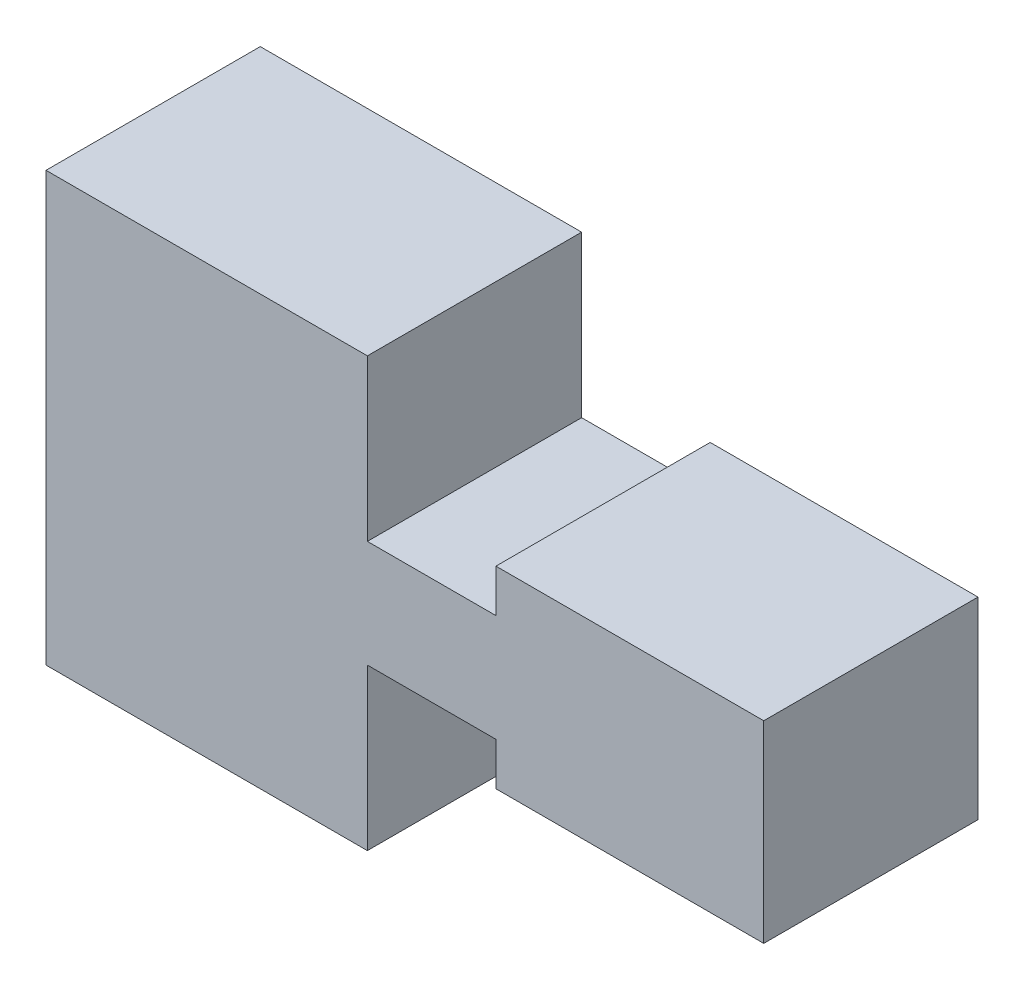
SolidWorks part; units mm, degrees
ref_plane "Front Plane" through (0, 0, 0) normal (0, 0, 1) x (1, 0, 0)
ref_plane "Top Plane" through (0, 0, 0) normal (0, 1, 0) x (1, 0, 0)
ref_plane "Right Plane" through (0, 0, 0) normal (1, 0, 0) x (0, 0, -1)
sketch "Sketch1" plane through (0, 0, 0) normal (0, 0, 1) x (1, 0, 0)
  line L0 (0, 0) -> (42.9561, 0) construction
  line L1 (-7.5, -10) -> (7.5, -10)
  line L2 (-7.5, -10) -> (-7.5, 10)
  line L3 (-7.5, 10) -> (7.5, 10)
  line L4 (7.5, -10) -> (7.5, 10)
  line L5 (-7.5, -10) -> (7.5, 10) construction
  line L6 (-7.5, 10) -> (7.5, -10) construction
  line L7 (7.5, 2.5) -> (13.5, 2.5)
  line L8 (7.5, 2.5) -> (7.5, -2.5)
  line L9 (7.5, -2.5) -> (13.5, -2.5)
  line L10 (13.5, 2.5) -> (13.5, -2.5)
  line L12 (13.5, -4.5) -> (26, -4.5)
  line L13 (13.5, -4.5) -> (13.5, 4.5)
  line L14 (13.5, 4.5) -> (26, 4.5)
  line L15 (26, -4.5) -> (26, 4.5)
  line L16 (13.5, -4.5) -> (26, 4.5) construction
  line L17 (13.5, 4.5) -> (26, -4.5) construction
  point P1 (0, 0)
  point P10 (19.75, 0)
  point P18 (0, 0)
  dimension "D1" = 20
  dimension "D2" = 5
  dimension "D3" = 15
  dimension "D4" = 6
  dimension "D5" = 12.5
  dimension "D6" = 2.5
  dimension "D7" = 2
extrude "Boss-Extrude1" add sketch "Sketch1" along normal blind 10 contours L1 L4 L3 L2 | L10 L7 L4 L9 | L12 L15 L14 L13 L10
sketch "Sketch5" plane through (-7.5, 0, 0) normal (-1, 0, 0) x (0, 0, 1)
  line L0 (0, -11.5) -> (10.0679, -11.5) construction
  line L1 (10, -10) -> (0, -10) construction
  line L2 (5, -10) -> (5, -12.7087) construction
  arc A0 (3.414, -10) -> (6.5745, -10) centre (4.9943, -7.8381) cw
  dimension "D1" = 1.5
  dimension "D2" = 3.414
